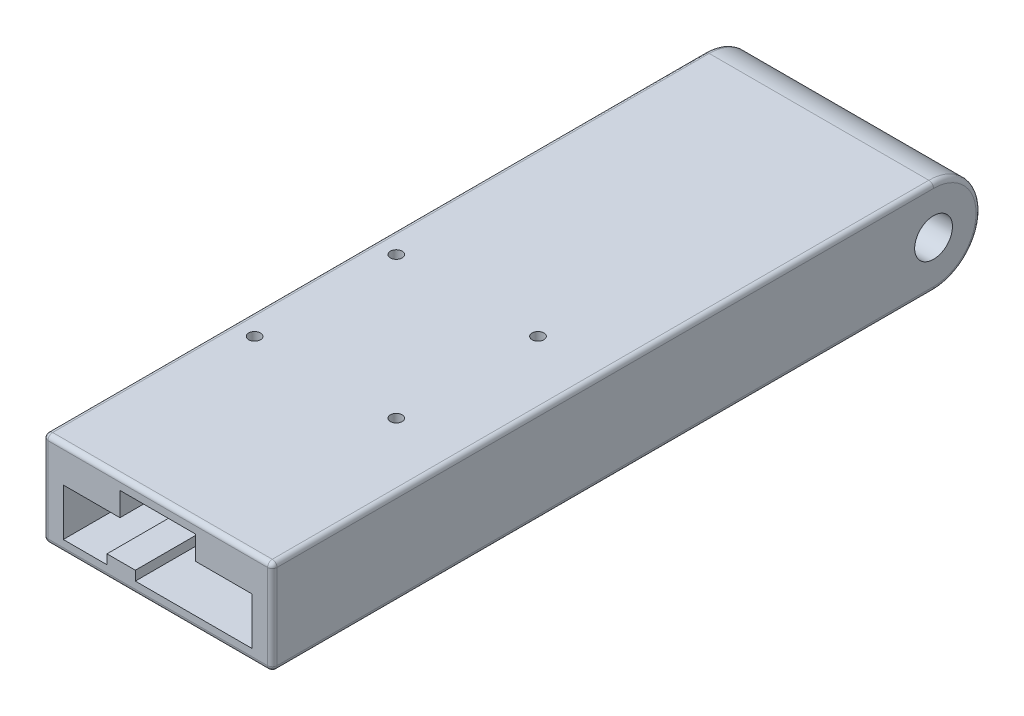
SolidWorks part; units mm, degrees
ref_plane "前视基准面" through (0, 0, 0) normal (0, 0, 1) x (1, 0, 0)
ref_plane "上视基准面" through (0, 0, 0) normal (0, 1, 0) x (1, 0, 0)
ref_plane "右视基准面" through (0, 0, 0) normal (1, 0, 0) x (0, 0, -1)
sketch "草图1" plane through (0, 0, 0) normal (0, 1, 0) x (1, 0, 0)
  line L1 (-24.25, 75) -> (24.25, 75)
  line L2 (-24.25, 75) -> (-24.25, -75)
  line L3 (-24.25, -75) -> (24.25, -75)
  line L4 (24.25, 75) -> (24.25, -75)
  line L5 (-24.25, 75) -> (24.25, -75) construction
  line L6 (-24.25, -75) -> (24.25, 75) construction
  point P0 (0, 0)
  dimension "D1" = 48.5
  dimension "D2" = 150
extrude "凸台-拉伸1" add sketch "草图1" along normal blind 20
sketch "草图3" plane through (24.25, 0, 0) normal (1, 0, 0) x (0, 0, -1)
  line L0 (65, 20) -> (65, 0) construction
  line L1 (-75, 20) -> (75, 20) construction
  line L2 (-75, 0) -> (75, 0) construction
  line L3 (75, 20) -> (75, 0) construction
  line L4 (65, 20) -> (75, 20)
  line L5 (75, 20) -> (75, 0)
  line L6 (75, 0) -> (65, 0)
  arc A0 (65, 20) -> (65, 0) centre (65, 10) cw
  point P8 (75, 10)
  line M1 (-75, 0) -> (75, 0)
  line M2 (75, 0) -> (75, 20)
  line M3 (75, 20) -> (-75, 20)
extrude "切除-拉伸1" cut sketch "草图3" against normal up to next contours A0 M2 M1 | A0 L5 M3
sketch "草图4" plane through (24.25, 0, 0) normal (1, 0, 0) x (0, 0, -1)
  line L0 (65, 20) -> (65, 0) construction
  circle A0 centre (65, 10) radius 4
  dimension "D1" = 8
extrude "切除-拉伸2" cut sketch "草图4" against normal up to next
sketch "草图5" plane through (0, 20, 0) normal (0, 1, 0) x (1, 0, 0)
  line L0 (0, 75) -> (0, -75) construction
  line L1 (24.25, 75) -> (-24.25, 75) construction
  line L2 (-24.25, -75) -> (24.25, -75) construction
  line L4 (-19.5, -5) -> (10.5, -5)
  line L5 (-19.5, -5) -> (-19.5, -35)
  line L6 (-19.5, -35) -> (10.5, -35)
  line L7 (10.5, -5) -> (10.5, -35)
  line L8 (-24.25, 65) -> (-24.25, -75) construction
  line L9 (-19.5, -5) -> (10.5, -35) construction
  dimension "D1" = 30
  dimension "D2" = 4.75
  dimension "D3" = 40
hole_wizard "M3x0.5 螺纹孔1" positions "3D草图1" profile "草图6" tap size "M3x0.5" standard "ANSI Metric"
sketch3d "3D草图1"
  point P0 (-19.5, 20, 5)
  point P3 (10.5, 20, 5)
  point P6 (-19.5, 20, 35)
  point P9 (10.5, 20, 35)
sketch "草图6" plane through (-19.5, 20, 5) normal (1, 0, 0) x (0, 0, 1)
  line L0 (0, 0) -> (0, 8.2511)
  line L1 (0, 8.2511) -> (1.25, 7.5)
  line L2 (1.25, 7.5) -> (1.25, 0)
  line L5 (1.25, 0) -> (0, 0)
  line L10 (0, 8.2511) -> (-1.25, 7.5) construction
  line L11 (0, -6.35) -> (0, 107.95) construction
  dimension "螺纹孔钻头直径" = 2.5
  dimension "螺纹孔钻头深度" = 7.5
  dimension "导头角度" = 118
cosmetic thread "孔螺蚊线1" parameters "D1"=6, "D2"=3
cosmetic thread "孔螺蚊线2" parameters "D1"=6, "D2"=3
cosmetic thread "孔螺蚊线3" parameters "D1"=6, "D2"=3
cosmetic thread "孔螺蚊线4" parameters "D1"=6, "D2"=3
sketch "草图9" plane through (-24.25, 0, 0) normal (-1, 0, 0) x (0, 0, 1)
  line L0 (24.1458, 0) -> (15.8542, 0)
  line L1 (24, 0) -> (16, 0) construction
  line L2 (-65, 0) -> (75, 0) construction
  arc A0 (24.1458, 0) -> (15.8542, 0) centre (20, -1.75) ccw
  dimension "D1" = 9
extrude "切除-拉伸3" cut sketch "草图9" against normal blind 14
sketch "草图10" plane through (-10.25, 0, 0) normal (-1, 0, 0) x (0, 0, 1)
  line L0 (28.8282, 0) -> (11.1718, 0)
  arc A0 (28.8282, 0) -> (11.1718, 0) centre (20, -1.75) ccw
  dimension "D1" = 18
extrude "切除-拉伸4" cut sketch "草图10" against normal blind 6 and the other way blind 1 contours A0 L0
sketch "草图11" plane through (0, 0, 75) normal (0, 0, 1) x (1, 0, 0)
  line L0 (-24.25, 0) -> (24.25, 20) construction
  line L1 (-4.7499, 2.159) -> (-10.7499, 2.159) construction
  line L2 (20, 2.5) -> (-20, 2.5)
  line L3 (20, 2.5) -> (20, 17.5)
  line L4 (20, 17.5) -> (-20, 17.5)
  line L5 (-20, 2.5) -> (-20, 17.5)
  line L6 (20, 2.5) -> (-20, 17.5) construction
  line L7 (20, 17.5) -> (-20, 2.5) construction
  line L8 (-26.65, -5.75) -> (-26.65, 2.25) construction
  line L9 (-26.65, -1.75) -> (-5.25, -1.75) construction
  line L10 (-4.7499, 4.5) -> (-10.7499, 4.5) construction
  line L11 (-10.7499, 4.5) -> (-10.7499, 0)
  line L12 (-24.25, 0) -> (24.25, 0) construction
  line L13 (-4.7499, 4.5) -> (-4.7499, 0)
  line L14 (-4.7499, 0) -> (-10.7499, 0)
  line L15 (-4.7499, 4.5) -> (-10.7499, 4.5)
  line L16 (-10.2499, 2.159) -> (-5.2499, 2.159) construction
  line L17 (8, 12.5) -> (8, 17.5)
  line L18 (8, 12.5) -> (20, 12.5)
  line L19 (20, 12.5) -> (20, 17.5)
  line L20 (20, 17.5) -> (8, 17.5)
  line L21 (0, 2.5) -> (0, 17.5) construction
  line L22 (-20, 12.5) -> (-20, 17.5)
  line L23 (-8, 12.5) -> (-20, 12.5)
  line L24 (-8, 12.5) -> (-8, 17.5)
  line L25 (-20, 17.5) -> (-8, 17.5)
  point P4 (0, 10)
  point P27 (-7.7499, 2.159)
  dimension "D1" = 40
  dimension "D2" = 15
  dimension "D3" = 6
  dimension "D4" = 5
  dimension "D5" = 12
  dimension "D6" = 4.5
  dimension "D7" = 6
extrude "切除-拉伸5" cut sketch "草图11" against normal blind 120 contours L24 L23 L5 L2 L11 L15 L13 L3 L18 L17 L4
fillet "圆角1" radius 1 11 edges at (24.25, 10, -75) (-24.25, 10, -75) (24.25, 0, 5) (0, 0, 75) (24.25, 20, 5) (-24.25, 20, 5) (0, 20, 75) (24.25, 10, 75) (-24.25, 10, 75) (-24.25, 0, -24.5729) (-24.25, 0, 49.5729)
